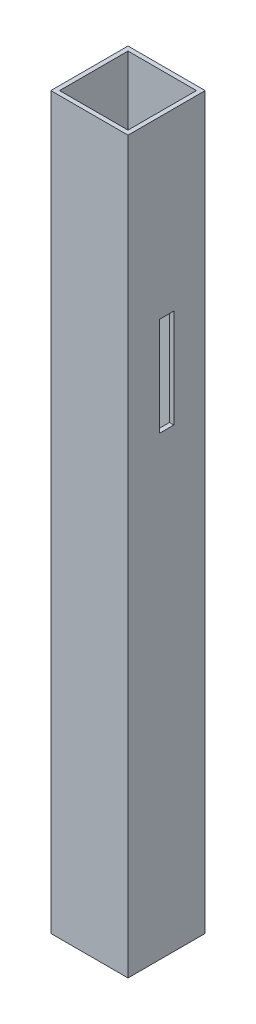
SolidWorks part; units mm, degrees
ref_plane "Front Plane" through (0, 0, 0) normal (0, 0, 1) x (1, 0, 0)
ref_plane "Top Plane" through (0, 0, 0) normal (0, 1, 0) x (1, 0, 0)
ref_plane "Right Plane" through (0, 0, 0) normal (1, 0, 0) x (0, 0, -1)
sketch "Sketch1" plane through (0, 0, 0) normal (0, 1, 0) x (1, 0, 0)
  line L1 (-17.4625, 17.4625) -> (17.4625, 17.4625)
  line L2 (-17.4625, 17.4625) -> (-17.4625, -17.4625)
  line L3 (-17.4625, -17.4625) -> (17.4625, -17.4625)
  line L4 (17.4625, 17.4625) -> (17.4625, -17.4625)
  line L5 (-17.4625, 17.4625) -> (17.4625, -17.4625) construction
  line L6 (-17.4625, -17.4625) -> (17.4625, 17.4625) construction
  line L7 (-15.4813, -15.4813) -> (15.4813, -15.4813)
  line L8 (-15.4813, -15.4813) -> (-15.4813, 15.4813)
  line L9 (-15.4813, 15.4813) -> (15.4813, 15.4813)
  line L10 (15.4813, -15.4813) -> (15.4813, 15.4813)
  line L11 (-15.4813, -15.4813) -> (15.4813, 15.4813) construction
  line L12 (-15.4813, 15.4813) -> (15.4813, -15.4813) construction
  point P0 (0, 0)
  point P5 (0, 0)
  dimension "D1" = 34.925
  dimension "D2" = 30.9626
extrude "Boss-Extrude1" add sketch "Sketch1" along normal mid plane 330.2
sketch "Sketch2" plane through (17.4625, 0, 0) normal (1, 0, 0) x (0, 0, -1)
  line L0 (-17.4625, 165.1) -> (17.4625, 165.1) construction
  line L1 (-3.275, 85.825) -> (3.275, 85.825)
  line L2 (-3.275, 85.825) -> (-3.275, 41.175)
  line L3 (-3.275, 41.175) -> (3.275, 41.175)
  line L4 (3.275, 85.825) -> (3.275, 41.175)
  line L5 (-3.275, 85.825) -> (3.275, 41.175) construction
  line L6 (-3.275, 41.175) -> (3.275, 85.825) construction
  point P0 (0, 63.5)
  dimension "D1" = 44.65
  dimension "D2" = 6.55
  dimension "D3" = 79.275
extrude "Cut-Extrude1" cut sketch "Sketch2" against normal through all
equation "\"D2@Sketch1\"=\"id\""
equation "\"D1@Sketch1\"=\"od\""
equation "\"od\"= 1.375in"
equation "\"id\"= \"od\" - ( .078 * 2 )"
equation "\"length\"= 13in"
equation "\"D1@Boss-Extrude1\"=\"length\""
equation "\"sheet thickness\"= .25in"
equation "\"tolerance\"= .2mm"
equation "\"D2@Sketch2\"=\"sheet thickness\"+\"tolerance\""
equation "\"slot width\"= 1.75in"
equation "\"D1@Sketch2\"=\"slot width\"+\"tolerance\""
equation "\"D3@Sketch2\"=3.125-(\"tolerance\"/2)"
